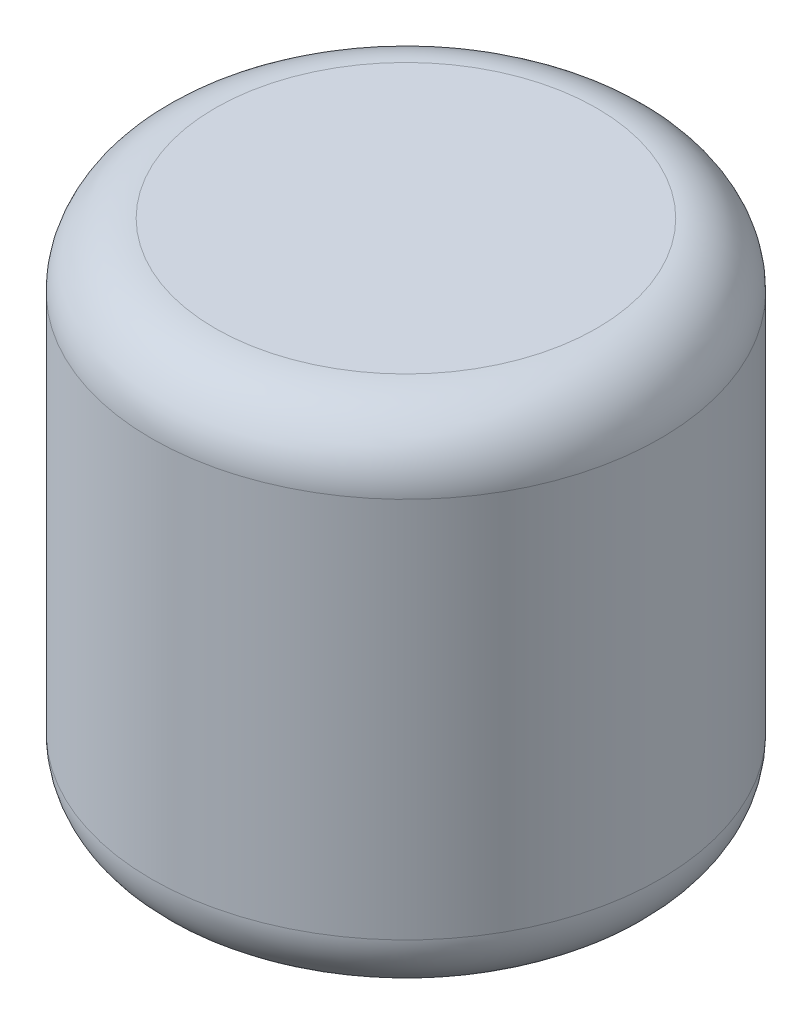
SolidWorks part; units mm, degrees
material "Сталь 45 ГОСТ 1050-88"
ref_plane "Спереди" through (0, 0, 0) normal (0, 0, 1) x (1, 0, 0)
ref_plane "Сверху" through (0, 0, 0) normal (0, 1, 0) x (1, 0, 0)
ref_plane "Справа" through (0, 0, 0) normal (1, 0, 0) x (0, 0, -1)
sketch "Эскиз1" plane through (0, 0, 0) normal (0, 1, 0) x (1, 0, 0)
  circle A0 centre (0, 0) radius 2
  dimension "D1" = 4
extrude "Бобышка-Вытянуть1" add sketch "Эскиз1" along normal mid plane 4
fillet "Скругление1" radius 0.5 2 edges at (0, -2, 2) (0, 2, 2)
